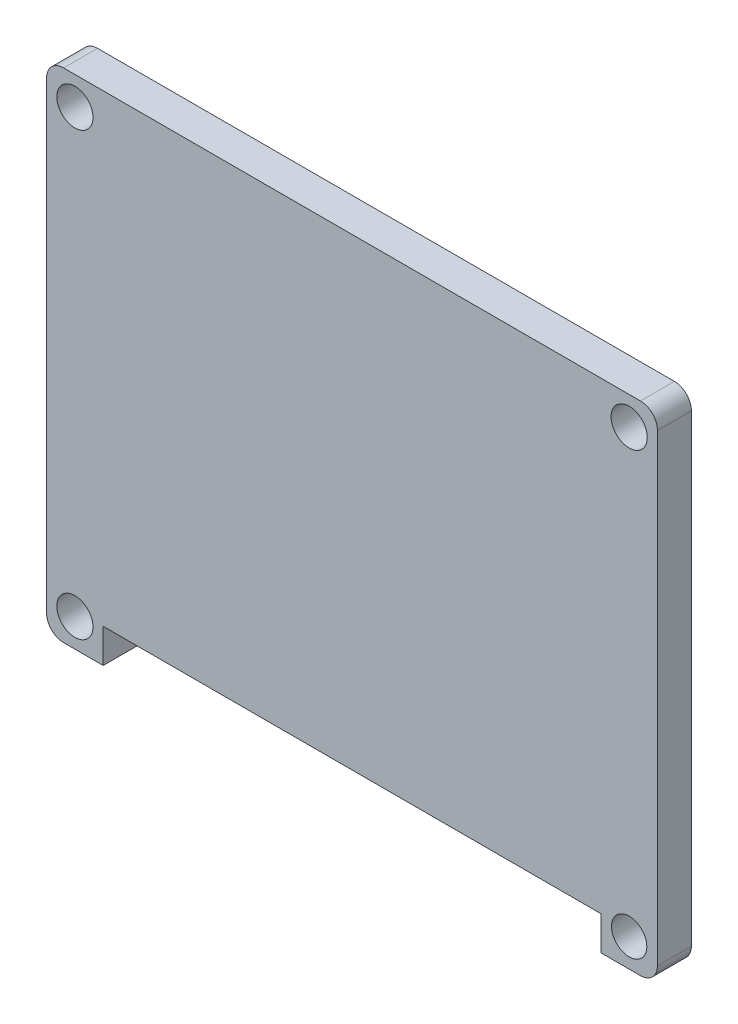
SolidWorks part; units mm, degrees
ref_plane "Front Plane" through (0, 0, 0) normal (0, 0, 1) x (1, 0, 0)
ref_plane "Top Plane" through (0, 0, 0) normal (0, 1, 0) x (1, 0, 0)
ref_plane "Right Plane" through (0, 0, 0) normal (1, 0, 0) x (0, 0, -1)
sketch "Sketch1" plane through (0, 0, 0) normal (0, 0, 1) x (1, 0, 0)
  line L10 (22.828, -22.0638) -> (21.828, -22.0638)
  line L11 (21.828, -22.0638) -> (21.828, -19.0638)
  line L12 (21.828, -19.0638) -> (-22.172, -19.0638)
  line L13 (-22.172, -19.0638) -> (-22.172, -22.0638)
  line L14 (-22.172, -22.0638) -> (-23.172, -22.0638)
  line L15 (-25.672, -22.0638) -> (-23.172, -22.0638)
  line L16 (22.828, -22.0638) -> (25.328, -22.0638)
  line L17 (26.828, -20.5638) -> (26.828, 20.4362)
  line L18 (25.328, 21.9362) -> (-25.672, 21.9362)
  line L19 (-27.172, 20.4362) -> (-27.172, -20.5638)
  circle A4 centre (-24.672, 19.4362) radius 1.6
  circle A5 centre (24.328, 19.4362) radius 1.6
  circle A6 centre (24.328, -19.5638) radius 1.5597
  circle A7 centre (-24.672, -19.5638) radius 1.6
  arc A8 (25.328, -22.0638) -> (26.828, -20.5638) centre (25.328, -20.5638) ccw
  arc A9 (26.828, 20.4362) -> (25.328, 21.9362) centre (25.328, 20.4362) ccw
  arc A10 (-25.672, 21.9362) -> (-27.172, 20.4362) centre (-25.672, 20.4362) ccw
  arc A11 (-27.172, -20.5638) -> (-25.672, -22.0638) centre (-25.672, -20.5638) ccw
extrude "Boss-Extrude1" add sketch "Sketch1" along normal mid plane 3
